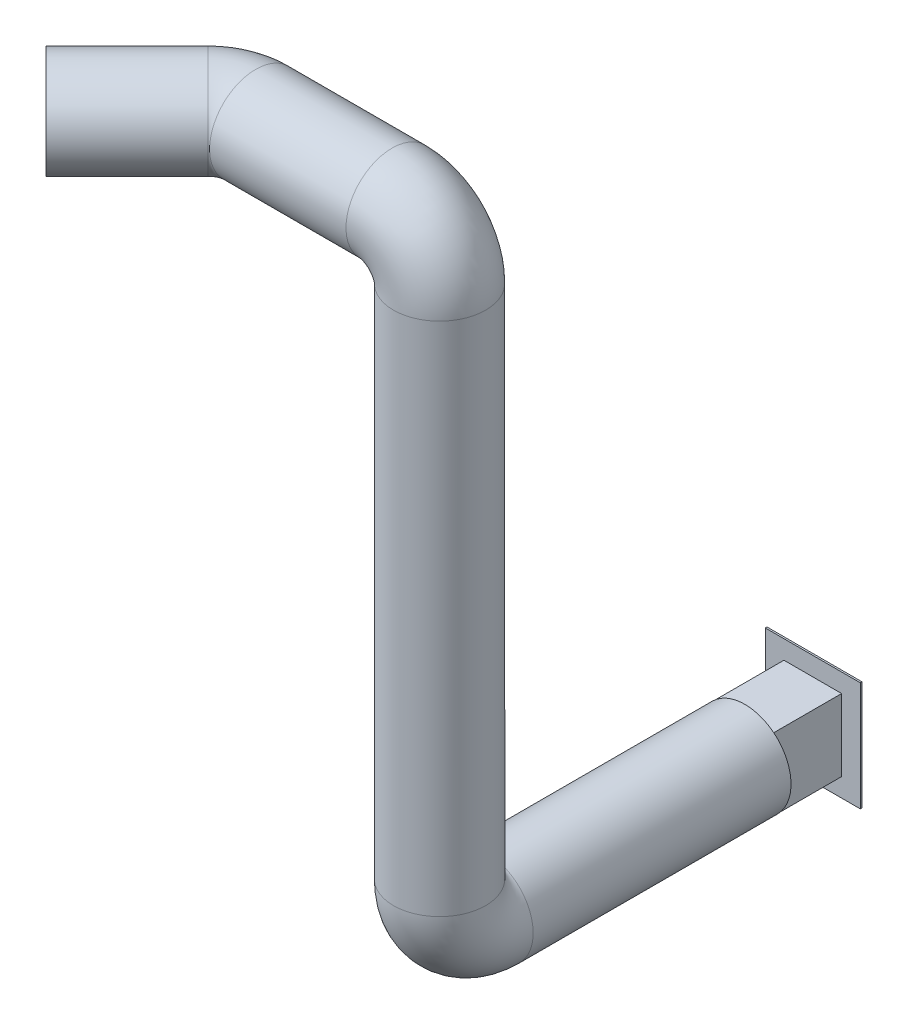
SolidWorks part; units mm, degrees
ref_plane "Alzado" through (0, 0, 0) normal (0, 0, 1) x (1, 0, 0)
ref_plane "Planta" through (0, 0, 0) normal (0, 1, 0) x (1, 0, 0)
ref_plane "Vista lateral" through (0, 0, 0) normal (1, 0, 0) x (0, 0, -1)
sketch "Croquis1" plane through (0, 0, 0) normal (0, 0, 1) x (1, 0, 0)
  line L0 (70, 0) -> (70, -161) construction
  line L1 (0, 0) -> (140, 0)
  line L2 (0, 0) -> (0, -161)
  line L3 (0, -161) -> (140, -161)
  line L4 (140, 0) -> (140, -161)
  line L6 (30, -131) -> (110, -131)
  line L7 (30, -131) -> (30, -30)
  line L8 (30, -30) -> (110, -30)
  line L9 (110, -131) -> (110, -30)
  line L10 (30, -131) -> (110, -30) construction
  line L11 (30, -30) -> (110, -131) construction
  point P8 (70, -80.5)
  dimension "D1" = 140
  dimension "D2" = 161
  dimension "D3" = 30
  dimension "D4" = 30
extrude "Saliente-Extruir1" add sketch "Croquis1" along normal blind 2.5
sketch "Croquis2" plane through (0, 0, 2.5) normal (0, 0, 1) x (1, 0, 0)
  line L0 (27.5, -27.5) -> (27.5, -133.5)
  line L1 (30, -30) -> (110, -30)
  line L2 (30, -30) -> (30, -131)
  line L3 (30, -131) -> (110, -131)
  line L4 (110, -30) -> (110, -131)
  line L5 (27.5, -133.5) -> (112.5, -133.5)
  line L6 (112.5, -27.5) -> (112.5, -133.5)
  line L7 (27.5, -27.5) -> (112.5, -27.5)
  dimension "D1" = 2.5
extrude "Saliente-Extruir2" add sketch "Croquis2" along normal blind 100
sketch "Croquis3" plane through (0, 0, 102.5) normal (0, 0, 1) x (1, 0, 0)
  line L0 (70, -27.5) -> (70, -133.5) construction
  line L1 (112.5, -27.5) -> (27.5, -27.5) construction
  line L2 (27.5, -133.5) -> (112.5, -133.5) construction
  circle A0 centre (70, -80.5) radius 67.9356
extrude "Saliente-Extruir3" add sketch "Croquis3" along normal blind 100
sketch3d "Croquis3D1"
  line L0 (70, -80.5, 202.5) -> (70, -80.5, 482.5)
  line L1 (70, -80.5, 202.5) -> (70, -80.5, 102.5) construction
  line L2 (70, -10.5, 552.5) -> (70, 749.5, 552.5)
  line L3 (0, 819.5, 552.5) -> (-201.0051, 819.5, 552.5)
  line L4 (-230, 819.5, 552.5) -> (-230, 819.5, 692.5) construction
  line L5 (-230, 819.5, 692.5) -> (-370, 819.5, 692.5) construction
  line L6 (-370, 819.5, 692.5) -> (-250.5025, 819.5, 573.0025)
  arc A0 (-201.0051, 819.5, 552.5) -> (-250.5025, 819.5, 573.0025) centre (-201.0051, 819.5, 622.5) ccw
  arc A1 (70, 749.5, 552.5) -> (0, 819.5, 552.5) centre (0, 749.5, 552.5) ccw
  arc A2 (70, -80.5, 482.5) -> (70, -10.5, 552.5) centre (70, -10.5, 482.5) ccw
  point P10 (-230, 819.5, 552.5)
  point P12 (-201.0051, 889.5, 622.5)
  point P15 (70, 819.5, 552.5)
  point P16 (0, 749.5, 622.5)
  point P19 (70, -80.5, 552.5)
  point P20 (0, -10.5, 482.5)
  dimension "D6" = 70
  dimension "D1" = 350
  dimension "D2" = 900
  dimension "D3" = 300
  dimension "D4" = 140
  dimension "D5" = 140
sketch "Croquis4" plane through (0, 0, 202.5) normal (0, 0, 1) x (1, 0, 0)
  circle A0 centre (70, -80.5) radius 67.9356
sweep "Barrer1" add profiles "Croquis4" path "Croquis3D1"
